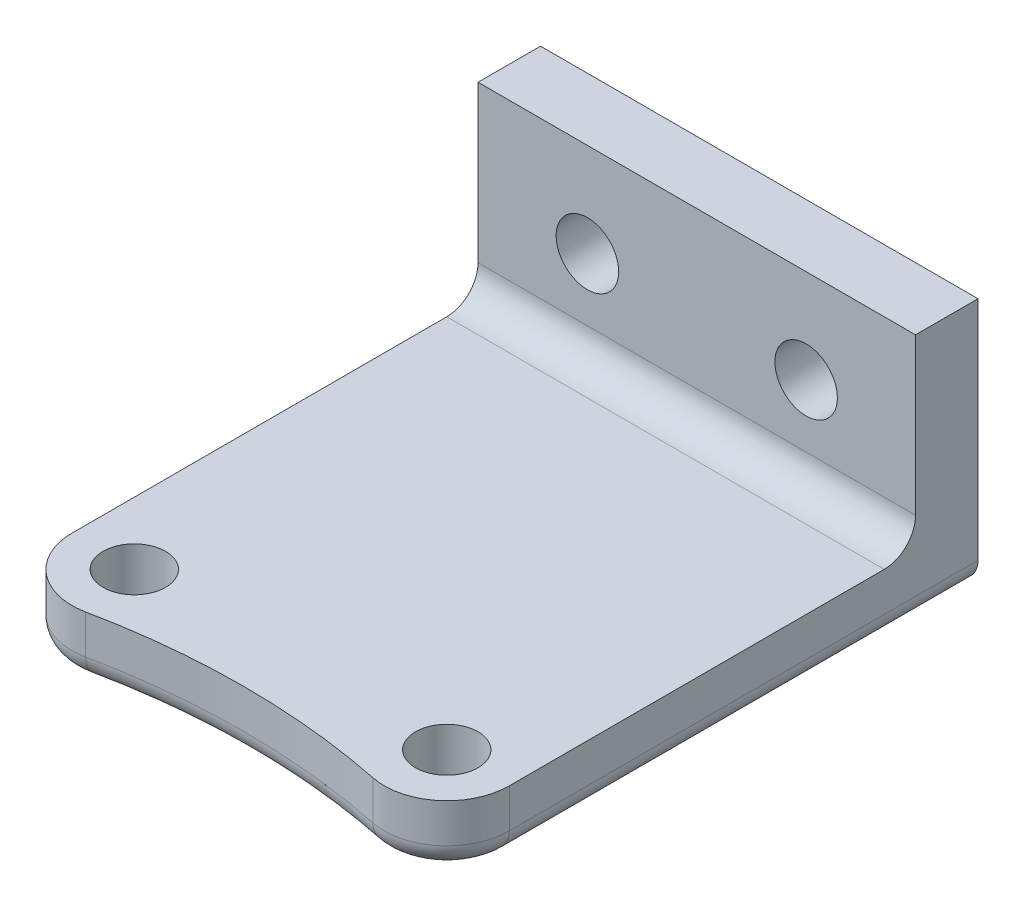
SolidWorks part; units mm, degrees
ref_plane "Front Plane" through (0, 0, 0) normal (0, 0, 1) x (1, 0, 0)
ref_plane "Top Plane" through (0, 0, 0) normal (0, 1, 0) x (1, 0, 0)
ref_plane "Right Plane" through (0, 0, 0) normal (1, 0, 0) x (0, 0, -1)
sketch "Sketch1" plane through (0, 0, 0) normal (0, 1, 0) x (1, 0, 0)
  line L0 (-4, 0) -> (-4, 30)
  line L1 (-4, 30) -> (24, 30)
  line L2 (24, 30) -> (24, 0)
  circle A0 centre (0, 0) radius 2
  circle A1 centre (20, 0) radius 2
  arc A3 (-4, 0) -> (0.8035, -3.9185) centre (0, 0) ccw
  arc A4 (19.1965, -3.9185) -> (24, 0) centre (20, 0) ccw
  arc A5 (19.1965, -3.9185) -> (0.8035, -3.9185) centre (10, -48.7663) ccw
extrude "Boss-Extrude1" add sketch "Sketch1" along normal blind 4
sketch "Sketch2" plane through (0, 4, 0) normal (0, 1, 0) x (1, 0, 0)
  line L0 (-4, 30) -> (-4, 26)
  line L1 (-4, 30) -> (-4, 0) construction
  line L2 (-4, 26) -> (24, 26)
  line L3 (24, 0) -> (24, 30) construction
  line L4 (24, 26) -> (24, 30)
  line L5 (24, 30) -> (-4, 30)
extrude "Boss-Extrude2" add sketch "Sketch2" along normal blind 12
sketch "Sketch3" plane through (0, 0, -26) normal (0, 0, 1) x (1, 0, 0)
  circle A0 centre (3, 10) radius 2
  circle A1 centre (17, 10) radius 2
extrude "Cut-Extrude1" cut sketch "Sketch3" against normal up to surface (4 mm away) up to face at (10, 8, -30)
fillet "Fillet1" radius 1.5 5 edges at (24, 0, -15) (22.5284, 0, 3.0995) (10, 0, 2.9853) (-2.5284, 0, 3.0995) (-4, 0, -15)
fillet "Fillet2" radius 2 1 edges at (10, 4, -26)
